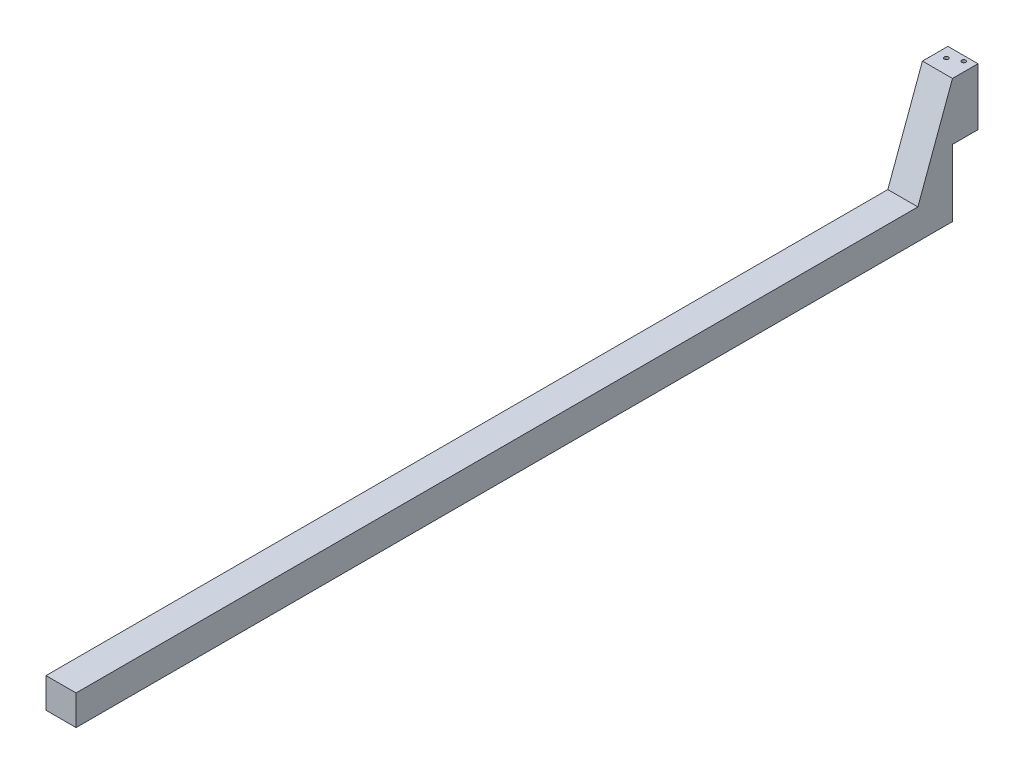
SolidWorks part; units mm, degrees
ref_plane "Front Plane" through (0, 0, 0) normal (0, 0, 1) x (1, 0, 0)
ref_plane "Top Plane" through (0, 0, 0) normal (0, 1, 0) x (1, 0, 0)
ref_plane "Right Plane" through (0, 0, 0) normal (1, 0, 0) x (0, 0, -1)
sketch "Sketch1" plane through (0, 0, 0) normal (0, 0, 1) x (1, 0, 0)
  line L1 (-4.4828, 10.9483) -> (15.5172, 10.9483)
  line L2 (-4.4828, 10.9483) -> (-4.4828, -71.5517)
  line L3 (-4.4828, -71.5517) -> (15.5172, -71.5517)
  line L4 (15.5172, 10.9483) -> (15.5172, -71.5517)
  dimension "D1" = 82.5
  dimension "D2" = 20
extrude "Boss-Extrude1" add sketch "Sketch1" along normal blind 600
sketch "Sketch2" plane through (0, 10.9483, 0) normal (0, 1, 0) x (1, 0, 0)
  line L0 (15.5172, 0) -> (-4.4828, -10.5753) construction
  line L1 (-4.4828, -600) -> (-4.4828, 0) construction
  circle A0 centre (9.3291, -3.2721) radius 1.35
  circle A1 centre (1.7054, -7.3032) radius 1.35
  dimension "D1" = 2.7
  dimension "D2" = 2.7
  dimension "D3" = 7
  dimension "D4" = 7
extrude "Cut-Extrude1" cut sketch "Sketch2" against normal blind 600
sketch "Sketch5" plane through (-4.4828, 0, 0) normal (-1, 0, 0) x (0, 0, 1)
  line L0 (0, 10.9483) -> (16.9695, 10.9483)
  line L1 (600, 10.9483) -> (0, 10.9483) construction
  line L2 (600, -71.5517) -> (600, -51.5517)
  line L3 (600, 10.9483) -> (600, -71.5517) construction
  line L4 (600, -51.5517) -> (40, -51.5517)
  line L5 (40, -51.5517) -> (16.9695, 10.9483)
  line L6 (600, 10.9483) -> (600, -51.5517)
  line L7 (16.9695, 10.9483) -> (600, 10.9483)
  line M6 (600, -71.5517) -> (600, 10.9483)
  line M7 (600, 10.9483) -> (0, 10.9483)
  dimension "D1" = 560
  dimension "D2" = 20
extrude "Cut-Extrude4" cut sketch "Sketch5" against normal blind 600 contours L5 L4 M6 M7
sketch "Sketch6" plane through (-4.4828, 0, 0) normal (-1, 0, 0) x (0, 0, 1)
  line L0 (16.9695, 10.9483) -> (16.9695, -71.5517) construction
  line L1 (600, -71.5517) -> (0, -71.5517) construction
  line L2 (0, -71.5517) -> (0, -27.0517)
  line L3 (0, 10.9483) -> (0, -71.5517) construction
  line L4 (0, -71.5517) -> (16.9695, -71.5517)
  line L5 (16.9695, -71.5517) -> (16.9695, -27.0517)
  line L6 (16.9695, -27.0517) -> (0, -27.0517)
  dimension "D1" = 44.5
extrude "Cut-Extrude5" cut sketch "Sketch6" against normal blind 600
sketch "Sketch7" plane through (0, -71.5517, 0) normal (0, -1, 0) x (1, 0, 0)
  circle A0 centre (0.5172, 550) radius 2
  circle A1 centre (0.5172, 535) radius 2
  point P6 (0.5172, 550)
  point P7 (0.5172, 535)
  point P14 (0.5172, 550)
  dimension "D3" = 4
  dimension "D4" = 4
  dimension "D2" = 15
sketch "Sketch10" plane through (0, -71.5517, 0) normal (0, -1, 0) x (1, 0, 0)
  line L0 (-4.4828, 600) -> (-4.4828, 16.9695) construction
  circle A0 centre (0.5172, 99.2462) radius 2
  circle A1 centre (0.5172, 84.2462) radius 2
  point P0 (0.5172, 99.2462)
  point P2 (0.5172, 84.2462)
  dimension "D1" = 4
  dimension "D2" = 15
  dimension "D3" = 5
sketch "Sketch11" plane through (0, -71.5517, 0) normal (0, -1, 0) x (1, 0, 0)
  line L0 (15.5172, 600) -> (15.5172, 16.9695) construction
  circle A0 centre (10.5172, 84.2462) radius 2
  circle A1 centre (10.5172, 99.2462) radius 2
  circle A2 centre (10.5172, 224.9093) radius 2
  circle A3 centre (10.5172, 239.9093) radius 2
  circle A4 centre (10.5172, 535) radius 2
  circle A5 centre (10.5172, 550) radius 2
  point P0 (10.5172, 84.2462)
  point P2 (10.5172, 99.2462)
  point P4 (10.5172, 224.9093)
  point P6 (10.5172, 239.9093)
  point P8 (10.5172, 535)
  point P10 (10.5172, 550)
  dimension "D1" = 4
  dimension "D2" = 4
  dimension "D3" = 4
  dimension "D4" = 4
  dimension "D5" = 4
  dimension "D6" = 4
  dimension "D7" = 15
  dimension "D8" = 15
  dimension "D9" = 15
  dimension "D10" = 5
  dimension "D11" = 5
  dimension "D12" = 5
hole_wizard "Ø4.0mm Dowel Hole3" positions "Sketch11" profile "Sketch14" hole size "Ø4.0" standard "AS"
sketch "Sketch14" plane through (10.5172, -71.5517, 84.2462) normal (1, 0, 0) x (0, 0, -1)
  line L0 (0, 0) -> (0, 15.2017)
  line L1 (0, 15.2017) -> (2, 14)
  line L2 (2, 14) -> (2, 0)
  line L5 (2, 0) -> (0, 0)
  line L10 (0, 15.2017) -> (-2, 14) construction
  line L11 (0, -6.35) -> (0, 107.95) construction
  dimension "Hole Dia." = 4
  dimension "Hole Depth" = 14
  dimension "Drill Angle" = 118
hole_wizard "Ø4.0mm Dowel Hole2" positions "Sketch7" profile "Sketch21" hole size "Ø4.0" standard "IS"
sketch "Sketch21" plane through (0.5172, -71.5517, 550) normal (1, 0, 0) x (0, 0, -1)
  line L0 (0, 0) -> (0, 15.2017)
  line L1 (0, 15.2017) -> (2, 14)
  line L2 (2, 14) -> (2, 0)
  line L5 (2, 0) -> (0, 0)
  line L10 (0, 15.2017) -> (-2, 14) construction
  line L11 (0, -6.35) -> (0, 107.95) construction
  dimension "Hole Dia." = 4
  dimension "Hole Depth" = 14
  dimension "Drill Angle" = 118
hole_wizard "Ø4.0mm Dowel Hole4" positions "Sketch10" profile "Sketch23" hole size "Ø4.0" standard "IS"
sketch "Sketch23" plane through (0.5172, -71.5517, 99.2462) normal (1, 0, 0) x (0, 0, -1)
  line L0 (0, 0) -> (0, 15.2017)
  line L1 (0, 15.2017) -> (2, 14)
  line L2 (2, 14) -> (2, 0)
  line L5 (2, 0) -> (0, 0)
  line L10 (0, 15.2017) -> (-2, 14) construction
  line L11 (0, -6.35) -> (0, 107.95) construction
  dimension "Hole Dia." = 4
  dimension "Hole Depth" = 14
  dimension "Drill Angle" = 118
sketch "Sketch24" plane through (0, -71.5517, 0) normal (0, -1, 0) x (1, 0, 0)
  circle A0 centre (0, 224.9093) radius 2
  circle A1 centre (0, 239.9093) radius 2
  point P0 (0, 224.9093)
  point P2 (0, 239.9093)
  dimension "D1" = 4
  dimension "D2" = 4
  dimension "D3" = 15
  dimension "D4" = 0
hole_wizard "Ø4.0mm Dowel Hole5" positions "Sketch24" profile "Sketch25" hole size "Ø4.0" standard "IS"
sketch "Sketch25" plane through (0, -71.5517, 224.9093) normal (1, 0, 0) x (0, 0, -1)
  line L0 (0, 0) -> (0, 15.2017)
  line L1 (0, 15.2017) -> (2, 14)
  line L2 (2, 14) -> (2, 0)
  line L5 (2, 0) -> (0, 0)
  line L10 (0, 15.2017) -> (-2, 14) construction
  line L11 (0, -6.35) -> (0, 107.95) construction
  dimension "Hole Dia." = 4
  dimension "Hole Depth" = 14
  dimension "Drill Angle" = 118
